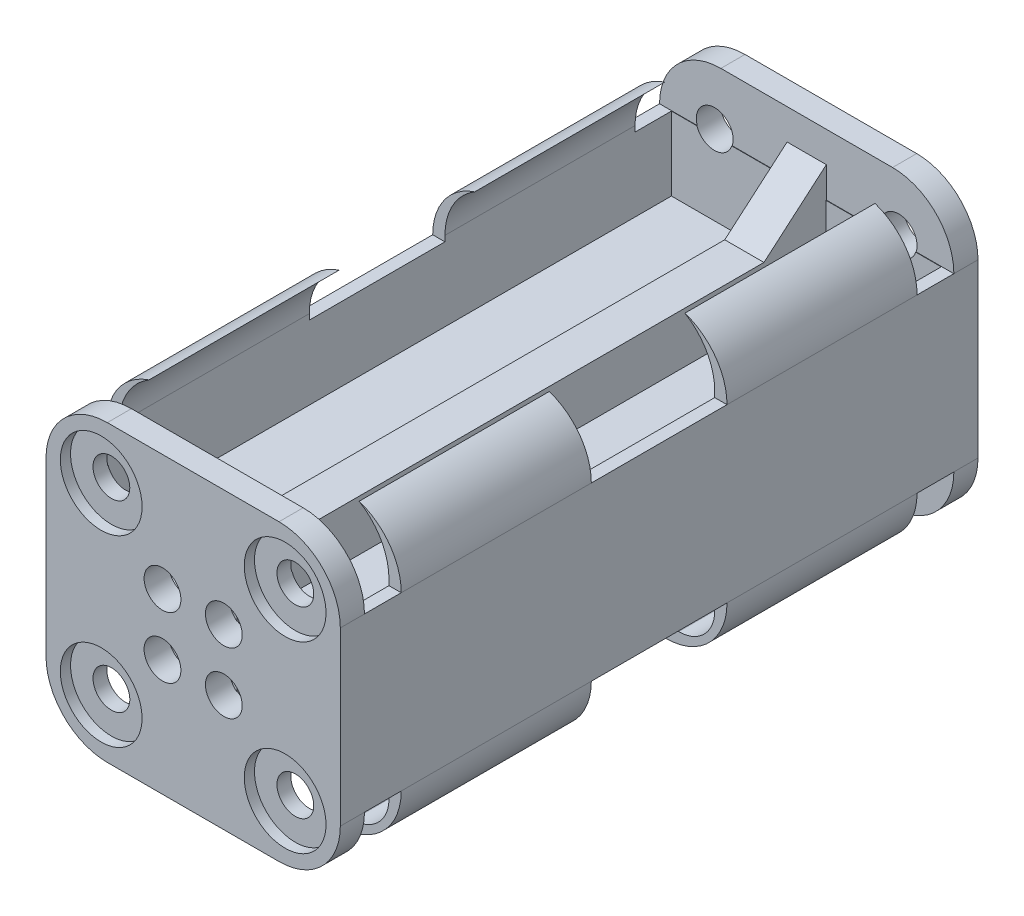
SolidWorks part; units mm, degrees
ref_plane "Plan de face" through (0, 0, 0) normal (0, 0, 1) x (1, 0, 0)
ref_plane "Plan de dessus" through (0, 0, 0) normal (0, 1, 0) x (1, 0, 0)
ref_plane "Plan de droite" through (0, 0, 0) normal (1, 0, 0) x (0, 0, -1)
sketch "Esquisse1" plane through (0, 0, 0) normal (0, 0, 1) x (1, 0, 0)
  line L0 (8.4, 0) -> (-8.4, 0)
  line L1 (0, 0) -> (8.4, 0)
  line L2 (-14.4, -6) -> (-14.4, -22.8)
  line L3 (-8.4, -28.8) -> (8.4, -28.8)
  line L4 (14.4, -22.8) -> (14.4, -6)
  arc A0 (8.4, 0) -> (14.4, -6) centre (8.4, -6) cw
  arc A1 (8.4, -28.8) -> (14.4, -22.8) centre (8.4, -22.8) ccw
  arc A2 (-14.4, -22.8) -> (-8.4, -28.8) centre (-8.4, -22.8) ccw
  arc A3 (-8.4, 0) -> (-14.4, -6) centre (-8.4, -6) ccw
  point P13 (-14.4, -28.8)
  point P16 (-14.4, 0)
  dimension "D1" = 6
  dimension "D2" = 6
  dimension "D4" = 6
  dimension "D5" = 6
  dimension "D3" = 28.8
extrude "Boss.-Extru.1" add sketch "Esquisse1" against normal blind 62.4 contours L0 A3 L2 A2 L3 A1 L4 A0
sketch "Esquisse2" plane through (0, 0, 0) normal (0, 1, 0) x (1, 0, 0)
  line L1 (0, 2.4) -> (-8.4, 2.4)
  line L2 (-8.4, 60) -> (-8.4, 2.4)
  line L3 (0, 60) -> (8.4, 60)
  line L4 (8.4, 62.4) -> (8.4, 0) construction
  line L5 (0, 60) -> (-8.4, 60)
  line L6 (-8.4, 62.4) -> (-8.4, 0) construction
  line L7 (0, 2.4) -> (8.4, 2.4)
  line L16 (8.4, 60) -> (8.4, 2.4)
extrude "Enlèv. mat.-Extru.1" cut sketch "Esquisse2" against normal blind 27.6
sketch "Esquisse4" plane through (14.4, 0, 0) normal (1, 0, 0) x (0, 0, -1)
  line L0 (2.3616, 0.5861) -> (2.3616, 8.7525) construction
  line L9 (59.8931, 3.0804) -> (59.8931, 17.0526) construction
  line L10 (2.3616, 4.1939) -> (5.9616, 4.1939)
  line L11 (2.3616, 4.1939) -> (2.3616, -6)
  line L13 (5.9616, 4.1939) -> (5.9616, -6)
  line L14 (31.2, -28.8) -> (31.2, 0) construction
  line L15 (62.4, -28.8) -> (0, -28.8) construction
  line L16 (2.4, 0) -> (60, 0) construction
  line L18 (56.4384, 4.1939) -> (56.4384, -6)
  line L19 (60.0384, 4.1939) -> (56.4384, 4.1939)
  line L20 (60.0384, 4.1939) -> (60.0384, -6)
  line L21 (5.9616, 4.1939) -> (24.5616, 4.1939) construction
  line L22 (24.5616, 4.1939) -> (31.1616, 4.1939)
  line L23 (24.5616, 4.1939) -> (24.5616, -6)
  line L25 (37.8384, 4.1939) -> (37.8384, -6)
  line L26 (37.8384, 4.1939) -> (31.2384, 4.1939)
  line L27 (2.3616, -6) -> (5.9616, -6)
  line L28 (24.5616, 4.1939) -> (37.8384, 4.1939)
  line L29 (24.5616, 4.1939) -> (24.5616, -6)
  line L31 (37.8384, 4.1939) -> (37.8384, -6)
  line L32 (62.4, -6) -> (0, -6) construction
  line L33 (24.5616, -6) -> (37.8384, -6)
  line L34 (24.5616, -6) -> (37.8384, -6)
  line L35 (0, -14.4) -> (62.4, -14.4) construction
  line L36 (24.5616, 4.1939) -> (37.8384, 4.1939)
  line L37 (24.5616, 4.1939) -> (24.5616, -6)
  line L38 (24.5616, -6) -> (37.8384, -6)
  line L39 (37.8384, 4.1939) -> (37.8384, -6)
  line L40 (56.4384, 4.1939) -> (60.0384, 4.1939)
  line L41 (56.4384, 4.1939) -> (56.4384, -6)
  line L42 (56.4384, -6) -> (60.0384, -6)
  line L43 (60.0384, 4.1939) -> (60.0384, -6)
  line L44 (0, -22.8) -> (0, -6) construction
  line L45 (62.4, -22.8) -> (62.4, -6) construction
  line L46 (56.4384, -22.8) -> (60.0384, -22.8)
  line L47 (60.0384, -32.9939) -> (60.0384, -22.8)
  line L48 (56.4384, -32.9939) -> (60.0384, -32.9939)
  line L49 (56.4384, -32.9939) -> (56.4384, -22.8)
  line L50 (24.5616, -22.8) -> (37.8384, -22.8)
  line L51 (37.8384, -32.9939) -> (37.8384, -22.8)
  line L52 (24.5616, -32.9939) -> (37.8384, -32.9939)
  line L53 (24.5616, -32.9939) -> (24.5616, -22.8)
  line L54 (2.3616, -32.9939) -> (2.3616, -22.8)
  line L55 (2.3616, -22.8) -> (5.9616, -22.8)
  line L56 (5.9616, -32.9939) -> (5.9616, -22.8)
  line L57 (2.3616, -32.9939) -> (5.9616, -32.9939)
  point P23 (31.2, -32.2467)
  line M26 (62.4, -6) -> (0, -6)
  dimension "D1" = 3.6
  dimension "D2" = 18.6
  dimension "D3" = 6.6
extrude "Enlèv. mat.-Extru.2" cut sketch "Esquisse4" against normal blind 62.4 contours L13 L10 L11 M26 | L28 L22 L23 L25 L26 M26 | L20 L19 L18 M26
sketch "Esquisse5" plane through (0, 0, 0) normal (0, 0, 1) x (1, 0, 0)
  line L0 (0, 0) -> (0, -28.8) construction
  line L1 (-8.4, -28.8) -> (8.4, -28.8) construction
  line L2 (-14.4, -14.4) -> (-13.2, -14.4) construction
  line L3 (-14.4, -6) -> (-14.4, -22.8) construction
  line L4 (14.4, -22.8) -> (14.4, -6) construction
  line L5 (0, -14.4) -> (0, -12.48) construction
  line L7 (-7.2, 0.5497) -> (7.2, 0.5497)
  line L8 (-13.2, -5.4503) -> (-13.2, -13.8503)
  line L10 (13.2, -5.4503) -> (13.2, -13.8503)
  line L11 (-13.2, 0.5497) -> (13.2, -13.8503) construction
  line L12 (-13.2, -13.8503) -> (13.2, 0.5497) construction
  line L13 (13.2, -23.3497) -> (13.2, -14.9497)
  line L15 (-13.2, -23.3497) -> (-13.2, -14.9497)
  line L16 (-13.2, -13.8503) -> (-13.2, -14.9497)
  line L17 (13.2, -13.8503) -> (13.2, -14.9497)
  line L18 (13.2, -14.4) -> (14.4, -14.4) construction
  line L22 (0, -28.8) -> (0, -27.6) construction
  line L23 (0, -27.6) -> (9.6659, -27.6)
  line L24 (13.2, -24.0659) -> (13.2, -23.3497)
  line L25 (0, -27.6) -> (-9.2, -27.6)
  line L26 (-13.2, -23.6) -> (-13.2, -23.3497)
  arc A0 (7.2, 0.5497) -> (13.2, -5.4503) centre (7.2, -5.4503) cw
  arc A1 (-7.2, 0.5497) -> (-13.2, -5.4503) centre (-7.2, -5.4503) ccw
  arc A2 (-9.2, -27.6) -> (-13.2, -23.6) centre (-9.2, -23.6) cw
  arc A3 (9.6659, -27.6) -> (13.2, -24.0659) centre (9.6659, -24.0659) ccw
  point P13 (0, -6.6503)
  dimension "D4" = 6
  dimension "D6" = 4
  dimension "D7" = 3.5341
  dimension "D1" = 1.92
  dimension "D2" = 26.4
  dimension "D3" = 14.4
  dimension "D5" = 1.2
extrude "Enlèv. mat.-Extru.5" cut sketch "Esquisse5" against normal up to surface (57.6 mm away) from offset 2.4 up to face at (0, -16.8, -60) offset against normal yes
sketch "Esquisse7" plane through (0, 0, 0) normal (0, 0, 1) x (1, 0, 0)
  line L0 (0, 0) -> (0, -28.8) construction
  line L1 (-8.4, -28.8) -> (8.4, -28.8) construction
  line L2 (-14.4, -14.4) -> (14.4, -14.4) construction
  line L3 (-14.4, -6) -> (-14.4, -22.8) construction
  line L4 (14.4, -22.8) -> (14.4, -6) construction
  line L5 (-7.3914, -4.6223) -> (-9, -4.6223) construction
  line L6 (-9, -3.6301) -> (-9, -5.4301) construction
  line L8 (-3, -11.4) -> (3, -11.4)
  line L9 (-3, -11.4) -> (-3, -17.4)
  line L10 (-3, -17.4) -> (3, -17.4)
  line L11 (3, -11.4) -> (3, -17.4)
  line L12 (-3, -11.4) -> (3, -17.4) construction
  line L13 (-3, -17.4) -> (3, -11.4) construction
  circle A0 centre (3, -11.4) radius 1.8
  circle A1 centre (-9, -5.4301) radius 1.8
  circle A2 centre (9, -5.4301) radius 1.8
  circle A3 centre (9, -23.3699) radius 1.8
  circle A4 centre (-9, -23.3699) radius 1.8
  circle A5 centre (-3, -11.4) radius 1.8
  circle A6 centre (3, -17.4) radius 1.8
  circle A7 centre (-3, -17.4) radius 1.8
  point P13 (0, -14.4)
  dimension "D3" = 3.6
  dimension "D4" = 3.6
  dimension "D1" = 6
  dimension "D2" = 6
extrude "Enlèv. mat.-Extru.8" cut sketch "Esquisse7" against normal blind 40 contours A5 | A0 | A6 | A7
sketch "Esquisse8" plane through (0, 0, 0) normal (0, 0, 1) x (1, 0, 0)
  line L0 (0, 0) -> (0, -28.8) construction
  line L1 (-8.4, -28.8) -> (8.4, -28.8) construction
  line L2 (-14.4, -14.4) -> (14.4, -14.4) construction
  line L3 (-14.4, -6) -> (-14.4, -22.8) construction
  line L4 (14.4, -22.8) -> (14.4, -6) construction
  line L6 (-9, -0.0301) -> (-9, -5.4301) construction
  arc A0 (-8.4, 0) -> (-14.4, -6) centre (-8.4, -6) ccw construction
  circle A1 centre (-9, -5.4301) radius 1.8
  circle A2 centre (9, -5.4301) radius 1.8
  circle A3 centre (9, -23.3699) radius 1.8
  circle A4 centre (-9, -23.3699) radius 1.8
  dimension "D3" = 3.6
  dimension "D2" = 5.4
extrude "Enlèv. mat.-Extru.9" cut sketch "Esquisse8" against normal blind 70
sketch "Esquisse9" plane through (0, 0, 0) normal (1, 0, 0) x (0, 0, -1)
  line L0 (2.3616, -6) -> (2.3616, -31.1744) construction
  line L1 (5.9616, -6) -> (5.9616, -31.1744) construction
  line L2 (24.5616, -5.4503) -> (24.5616, -31.1744) construction
  line L3 (37.8384, -6) -> (37.8384, -31.1744) construction
  line L4 (37.8384, -6) -> (24.5616, -6) construction
  line L5 (56.4384, -6) -> (56.4384, -31.1744) construction
  line L6 (60.0384, -6) -> (60.0384, -31.1744) construction
  line L7 (62.4, -22.8) -> (0, -22.8) construction
  line L8 (2.3616, -22.8) -> (5.9616, -22.8)
  line L9 (2.3616, -22.8) -> (2.3616, -31.1744)
  line L10 (2.3616, -31.1744) -> (5.9616, -31.1744)
  line L11 (5.9616, -22.8) -> (5.9616, -31.1744)
  line L13 (24.5616, -22.8) -> (37.8384, -22.8)
  line L14 (24.5616, -22.8) -> (24.5616, -34.5091)
  line L15 (24.5616, -34.5091) -> (37.8384, -34.5091)
  line L16 (37.8384, -22.8) -> (37.8384, -34.5091)
  line L17 (56.4384, -22.8) -> (60.0384, -22.8)
  line L18 (56.4384, -22.8) -> (56.4384, -33.8018)
  line L19 (56.4384, -33.8018) -> (60.0384, -33.8018)
  line L20 (60.0384, -22.8) -> (60.0384, -33.8018)
extrude "Enlèv. mat.-Extru.10" cut sketch "Esquisse9" against normal blind 70 and the other way blind 70
sketch "Esquisse10" plane through (0, 0, 0) normal (0, 0, 1) x (1, 0, 0)
  line L0 (-14.4, -14.4) -> (14.4, -14.4) construction
  line L1 (-14.4, -6) -> (-14.4, -22.8) construction
  line L2 (14.4, -22.8) -> (14.4, -6) construction
  line L3 (-14.4, -14.4) -> (-14.4, -13.2)
  line L4 (-14.4, -14.4) -> (-14.4, -15.6)
  line L6 (-14.4, -13.2) -> (14.4, -13.2)
  line L7 (-14.4, -13.2) -> (-14.4, -15.6)
  line L8 (-14.4, -15.6) -> (14.4, -15.6)
  line L9 (14.4, -13.2) -> (14.4, -15.6)
  dimension "D1" = 1.2
  dimension "D2" = 1.2
extrude "Boss.-Extru.2" add sketch "Esquisse10" against normal up to surface (60 mm away) contours L7 L6 L9 L8 up to face at (0, -14.4, -60)
sketch "Esquisse11" plane through (0, 0, 0) normal (0, 1, 0) x (1, 0, 0)
sketch "Esquisse12" plane through (0, -28.8, 0) normal (0, -1, 0) x (1, 0, 0)
  line L1 (-8.4, -37.8384) -> (8.4, -37.8384)
  line L2 (-8.4, -37.8384) -> (-8.4, -56.4384)
  line L3 (-8.4, -56.4384) -> (8.4, -56.4384)
  line L4 (8.4, -37.8384) -> (8.4, -56.4384)
  line L5 (-8.4, -5.9616) -> (8.4, -5.9616)
  line L6 (-8.4, -5.9616) -> (-8.4, -24.5616)
  line L7 (-8.4, -24.5616) -> (8.4, -24.5616)
  line L8 (8.4, -5.9616) -> (8.4, -24.5616)
extrude "Enlèv. mat.-Extru.11" cut sketch "Esquisse12" against normal blind 4
sketch "Esquisse13" plane through (0, 0, 0) normal (1, 0, 0) x (0, 0, -1)
  line L0 (60.0384, -3) -> (53.9364, -8.2359)
  line L3 (60.0384, 0) -> (60.0384, -6) construction
  line L4 (31.2, -6) -> (31.2, -26.9303) construction
  line L5 (37.8384, -6) -> (24.5616, -6) construction
  line L6 (2.3616, -3) -> (8.4636, -8.2359)
  line L7 (8.4636, -8.2359) -> (53.9364, -8.2359)
  line L9 (0, -14.4) -> (62.4, -14.4) construction
  line L10 (0, -6) -> (0, -22.8) construction
  line L11 (62.4, -6) -> (62.4, -22.8) construction
  line L12 (8.4636, -20.5641) -> (53.9364, -20.5641)
  line L13 (60.0384, -25.8) -> (53.9364, -20.5641)
  line L14 (2.3616, -25.8) -> (8.4636, -20.5641)
  line L15 (2.3616, -3) -> (2.3616, -25.8)
  line L16 (60.0384, -3) -> (60.0384, -25.8)
extrude "Boss.-Extru.3" add sketch "Esquisse13" along normal blind 1.92 and the other way blind 1.92
sketch "Esquisse14" plane through (0, 0, 0) normal (0, 0, 1) x (1, 0, 0)
  line L0 (0, 0) -> (0, -28.8) construction
  line L1 (-8.4, -28.8) -> (8.4, -28.8) construction
  line L2 (-14.4, -14.4) -> (14.4, -14.4) construction
  line L3 (-14.4, -6) -> (-14.4, -22.8) construction
  line L4 (14.4, -22.8) -> (14.4, -6) construction
  circle A0 centre (-9, -5.4301) radius 4
  circle A1 centre (9, -5.4301) radius 4
  circle A2 centre (9, -23.3699) radius 4
  circle A3 centre (-9, -23.3699) radius 4
  dimension "D1" = 8
extrude "Enlèv. mat.-Extru.12" cut sketch "Esquisse14" against normal blind 1
